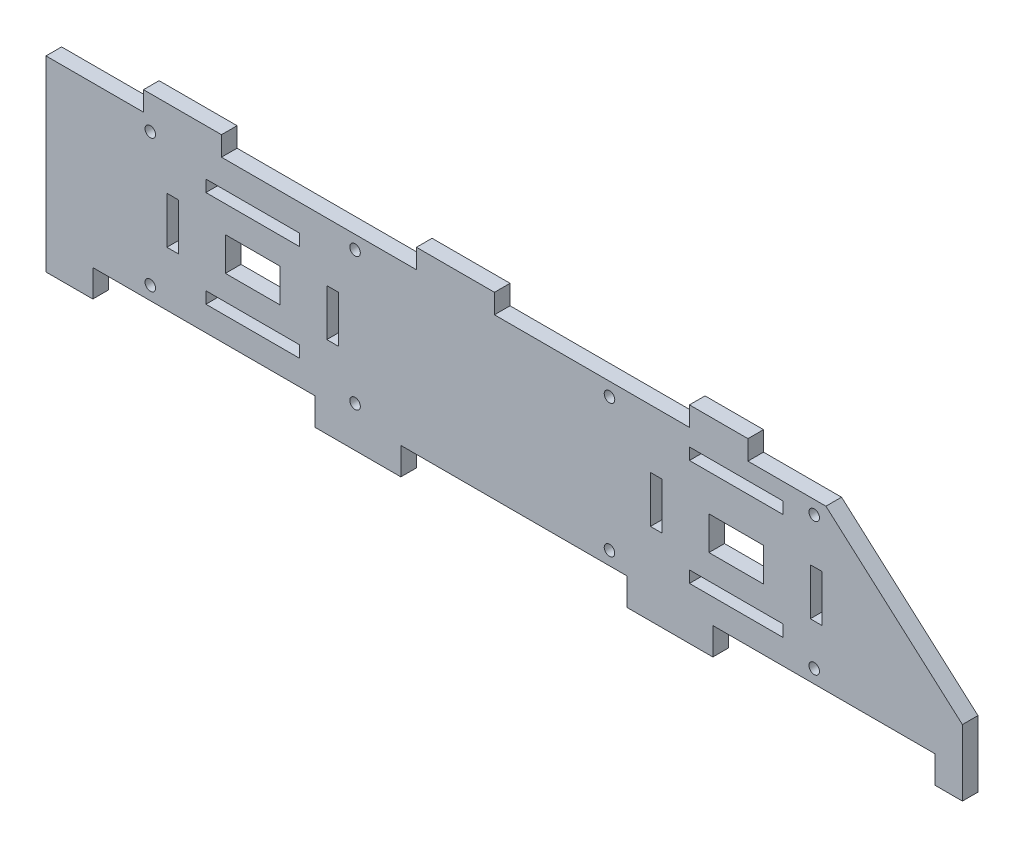
SolidWorks part; units mm, degrees
ref_plane "Front Plane" through (0, 0, 0) normal (0, 0, 1) x (1, 0, 0)
ref_plane "Top Plane" through (0, 0, 0) normal (0, 1, 0) x (1, 0, 0)
ref_plane "Right Plane" through (0, 0, 0) normal (1, 0, 0) x (0, 0, -1)
sketch "Sketch1" plane through (0, 0, 0) normal (0, 0, 1) x (1, 0, 0)
  line L2 (-105.5, 0) -> (-48.5, 0)
  line L4 (-117.5, 0) -> (-117.5, 41)
  line L6 (117.5, 0) -> (117.5, 10)
  line L7 (117.5, 10) -> (82.5, 41)
  line L8 (110.5, 0) -> (110.5, -7)
  line L9 (110.5, -7) -> (117.5, -7)
  line L10 (117.5, -7) -> (117.5, 0)
  line L11 (-26.5, 0) -> (31.5, 0)
  line L12 (53.5, 0) -> (53.5, -7)
  line L13 (53.5, -7) -> (31.5, -7)
  line L14 (31.5, -7) -> (31.5, 0)
  line L16 (53.5, 0) -> (110.5, 0)
  line L17 (-26.5, 0) -> (-26.5, -7)
  line L18 (-26.5, -7) -> (-48.5, -7)
  line L19 (-48.5, -7) -> (-48.5, 0)
  line L22 (-105.5, 0) -> (-105.5, -7)
  line L23 (-105.5, -7) -> (-117.5, -7)
  line L24 (-117.5, -7) -> (-117.5, 0)
  line L25 (-117.5, 41) -> (-92.5, 41)
  line L26 (-92.5, 41) -> (-92.5, 46)
  line L27 (-92.5, 46) -> (-72.5, 46)
  line L28 (-72.5, 46) -> (-72.5, 41)
  line L29 (-72.5, 41) -> (-22.5, 41)
  line L30 (-22.5, 41) -> (-22.5, 46)
  line L31 (-22.5, 46) -> (-2.5, 46)
  line L32 (-2.5, 46) -> (-2.5, 41)
  line L33 (-2.5, 41) -> (47.5, 41)
  line L34 (47.5, 41) -> (47.5, 46)
  line L35 (47.5, 46) -> (62.5, 46)
  line L36 (62.5, 46) -> (62.5, 41)
  line L37 (62.5, 41) -> (82.5, 41)
  dimension "D2" = 200
  dimension "D3" = 25
  dimension "D4" = 5
  dimension "D5" = 41
  dimension "D6" = 10
  dimension "D7" = 7
  dimension "D8" = 7
  dimension "D9" = 7
  dimension "D10" = 57
  dimension "D11" = 7
  dimension "D12" = 22
  dimension "D13" = 58
  dimension "D14" = 7
  dimension "D15" = 22
  dimension "D16" = 12
  dimension "D17" = 7
  dimension "D18" = 12
  dimension "D19" = 20
  dimension "D20" = 5
  dimension "D21" = 50
  dimension "D22" = 5
  dimension "D23" = 20
  dimension "D24" = 5
  dimension "D25" = 50
  dimension "D26" = 5
  dimension "D27" = 15
  dimension "D28" = 5
extrude "Boss-Extrude2" add sketch "Sketch1" along normal blind 4 contours L23 L24 L4 L25 L26 L27 L28 L29 L30 L31 L32 L33 L34 L35 L36 L37 L7 L6 L10 L9 L8 L16 L12 L13 L14 L11 L17 L18 L19 L2 L22
sketch "Sketch2" plane through (0, 0, 4) normal (0, 0, 1) x (1, 0, 0)
  line L8 (-71.5, 20) -> (-71.5, 24.3)
  line L9 (-71.5, 24.3) -> (-57.5, 24.3)
  line L10 (-57.5, 24.3) -> (-57.5, 15.7)
  line L11 (-57.5, 15.7) -> (-71.5, 15.7)
  line L12 (-71.5, 15.7) -> (-71.5, 20)
  line L14 (52.5, 20) -> (52.5, 24.3)
  line L15 (52.5, 24.3) -> (66.5, 24.3)
  line L16 (66.5, 24.3) -> (66.5, 15.7)
  line L17 (66.5, 15.7) -> (52.5, 15.7)
  line L18 (52.5, 15.7) -> (52.5, 20)
  dimension "D2" = 4.3
  dimension "D3" = 14
  dimension "D4" = 8.6
  dimension "D6" = 4.3
  dimension "D7" = 14
  dimension "D8" = 8.6
  dimension "D9" = 14
extrude "Cut-Extrude1" cut sketch "Sketch2" against normal up to surface (4 mm away) up to face at (-1.6379, 19.2414, 0)
sketch "Sketch4" plane through (0, 0, 4) normal (0, 0, 1) x (1, 0, 0)
  line L7 (-90.75, 20.5) -> (-90.75, 37.55)
  line L8 (-90.75, 37.55) -> (-38.25, 37.55)
  line L9 (-38.25, 37.55) -> (-38.25, 3.45)
  line L12 (-38.25, 3.45) -> (-90.75, 3.45)
  line L13 (-90.75, 3.45) -> (-90.75, 20.5)
  line L14 (59.5, 24.3) -> (59.5, 0)
  line L15 (66.5, 24.3) -> (52.5, 24.3) construction
  line L16 (53.5, 0) -> (110.5, 0) construction
  line L18 (79.5, 20.5) -> (79.5, 3.45)
  line L19 (79.5, 3.45) -> (27, 3.45)
  line L20 (27, 3.45) -> (27, 37.55)
  line L21 (27, 37.55) -> (79.5, 37.55)
  line L22 (79.5, 37.55) -> (79.5, 20.5)
  circle A0 centre (-38.25, 37.55) radius 1.35
  circle A1 centre (-90.75, 37.55) radius 1.35
  circle A2 centre (-90.75, 3.45) radius 1.35
  circle A3 centre (-38.25, 3.45) radius 1.35
  circle A4 centre (27, 37.55) radius 1.35
  circle A5 centre (79.5, 37.55) radius 1.35
  circle A6 centre (79.5, 3.45) radius 1.35
  circle A7 centre (27, 3.45) radius 1.35
  dimension "D6" = 2.7
  dimension "D11" = 2.7
  dimension "D12" = 2.7
  dimension "D13" = 2.7
  dimension "D14" = 2.7
  dimension "D15" = 2.7
  dimension "D16" = 2.7
  dimension "D17" = 2.7
  dimension "D2" = 17.05
  dimension "D3" = 52.5
  dimension "D4" = 34.1
  dimension "D5" = 52.5
  dimension "D7" = 17.05
  dimension "D8" = 52.5
  dimension "D9" = 34.1
  dimension "D10" = 52.5
extrude "Cut-Extrude2" cut sketch "Sketch4" against normal up to surface (4 mm away) contours A1 | A2 | A3 | A0 | A4 | A7 | A6 | A5 up to face at (-64.5, 20, 0)
sketch "Sketch6" plane through (0, 0, 4) normal (0, 0, 1) x (1, 0, 0)
  line L0 (-90.75, 3.45) -> (-90.75, 37.55)
  line L1 (-90.75, 37.55) -> (86.3952, 37.55)
  line L2 (117.5, 10) -> (82.5, 41) construction
  line L3 (-90.75, 3.45) -> (117.5, 3.45)
  line L4 (117.5, -7) -> (117.5, 10) construction
  line L5 (-71.5, 24.3) -> (-90.75, 24.3)
  line L6 (-90.75, 24.3) -> (-71.5, 24.3)
  line L7 (-71.5, 15.7) -> (-90.75, 15.7)
  line L8 (-90.75, 15.7) -> (111.0645, 15.7)
  line L9 (-57.5, 24.3) -> (-71.5, 24.3)
  line L10 (-64.5, 24.3) -> (-64.5, 31.15)
  line L11 (-72.5, 41) -> (-22.5, 41) construction
  line L12 (-64.5, 15.7) -> (-64.5, 24.3)
  line L13 (52.5, 24.3) -> (66.5, 24.3)
  line L14 (66.5, 24.3) -> (59.5, 24.3)
  line L15 (59.5, 24.3) -> (59.5, 33.65)
  line L16 (-64.5, 41) -> (-64.5, 34.15)
  line L17 (-64.5, 6.35) -> (-64.5, 0)
  line L19 (-76.5, 34.15) -> (-52.5, 34.15)
  line L20 (-52.5, 34.15) -> (-52.5, 31.15)
  line L21 (-52.5, 31.15) -> (-76.5, 31.15)
  line L23 (-71.5, 15.7) -> (-57.5, 15.7)
  line L24 (-57.5, 15.7) -> (-64.5, 15.7)
  line L25 (-64.5, 15.7) -> (-64.5, 9.35)
  line L26 (-105.5, 0) -> (-48.5, 0) construction
  line L27 (-64.5, 0) -> (-64.5, 6.35)
  line L28 (59.5, 36.65) -> (59.5, 46)
  line L30 (-52.5, 9.35) -> (-76.5, 9.35)
  line L31 (-76.5, 9.35) -> (-76.5, 6.35)
  line L32 (-76.5, 6.35) -> (-52.5, 6.35)
  line L34 (47.5, 46) -> (62.5, 46) construction
  line L35 (59.5, 46) -> (59.5, 36.65)
  line L36 (59.5, 6.35) -> (59.5, 0)
  line L38 (47.5, 36.65) -> (71.5, 36.65)
  line L39 (71.5, 36.65) -> (71.5, 33.65)
  line L40 (71.5, 33.65) -> (47.5, 33.65)
  line L42 (66.5, 15.7) -> (52.5, 15.7)
  line L43 (52.5, 15.7) -> (59.5, 15.7)
  line L44 (59.5, 15.7) -> (59.5, 9.35)
  line L45 (53.5, 0) -> (110.5, 0) construction
  line L46 (59.5, 0) -> (59.5, 6.35)
  line L47 (-76.5, 31.15) -> (-76.5, 34.15)
  line L49 (71.5, 9.35) -> (47.5, 9.35)
  line L50 (47.5, 9.35) -> (47.5, 6.35)
  line L51 (47.5, 6.35) -> (71.5, 6.35)
  line L53 (-71.5, 20) -> (-83.5, 20)
  line L54 (-83.5, 20) -> (-83.5, 26)
  line L55 (-83.5, 26) -> (-86.5, 26)
  line L56 (-86.5, 26) -> (-86.5, 14)
  line L57 (-86.5, 14) -> (-83.5, 14)
  line L58 (-83.5, 14) -> (-83.5, 20)
  line L59 (-57.5, 20) -> (-45.5, 20)
  line L60 (-45.5, 20) -> (-45.5, 26)
  line L61 (-45.5, 26) -> (-42.5, 26)
  line L62 (-42.5, 26) -> (-42.5, 14)
  line L63 (-42.5, 14) -> (-45.5, 14)
  line L64 (-45.5, 14) -> (-45.5, 20)
  line L65 (52.5, 20) -> (40.5, 20)
  line L66 (40.5, 20) -> (40.5, 26)
  line L67 (40.5, 26) -> (37.5, 26)
  line L68 (37.5, 26) -> (37.5, 14)
  line L69 (37.5, 14) -> (40.5, 14)
  line L70 (40.5, 14) -> (40.5, 20)
  line L71 (66.5, 20) -> (78.5, 20)
  line L72 (78.5, 20) -> (78.5, 26)
  line L73 (78.5, 26) -> (81.5, 26)
  line L74 (81.5, 26) -> (81.5, 14)
  line L75 (81.5, 14) -> (78.5, 14)
  line L76 (78.5, 14) -> (78.5, 20)
  line L77 (-64.5, 34.15) -> (-64.5, 41)
  line L78 (-52.5, 9.35) -> (-52.5, 6.35)
  line L79 (47.5, 33.65) -> (47.5, 36.65)
  line L80 (71.5, 6.35) -> (71.5, 9.35)
  dimension "D36" = 3
  dimension "D3" = 24
  dimension "D4" = 3
  dimension "D5" = 24
  dimension "D8" = 24
  dimension "D9" = 3
  dimension "D10" = 24
  dimension "D13" = 24
  dimension "D14" = 3
  dimension "D17" = 24
  dimension "D18" = 3
  dimension "D19" = 12
  dimension "D20" = 6
  dimension "D21" = 3
  dimension "D22" = 12
  dimension "D23" = 3
  dimension "D24" = 12
  dimension "D25" = 6
  dimension "D26" = 3
  dimension "D27" = 12
  dimension "D28" = 3
  dimension "D29" = 12
  dimension "D30" = 6
  dimension "D31" = 3
  dimension "D32" = 12
  dimension "D33" = 3
  dimension "D34" = 12
  dimension "D35" = 6
  dimension "D37" = 12
  dimension "D38" = 3
extrude "Cut-Extrude3" cut sketch "Sketch6" against normal up to surface (4 mm away) contours L78 L32 L31 L30 | L47 L19 L20 L21 | L40 L79 L38 L39 | L80 L49 L50 L51 | L60 L61 L62 L63 L64 | L54 L55 L56 L57 L58 | L72 L73 L74 L75 L76 | L66 L67 L68 L69 L70 up to face at (-92.1, 3.45, 0)
